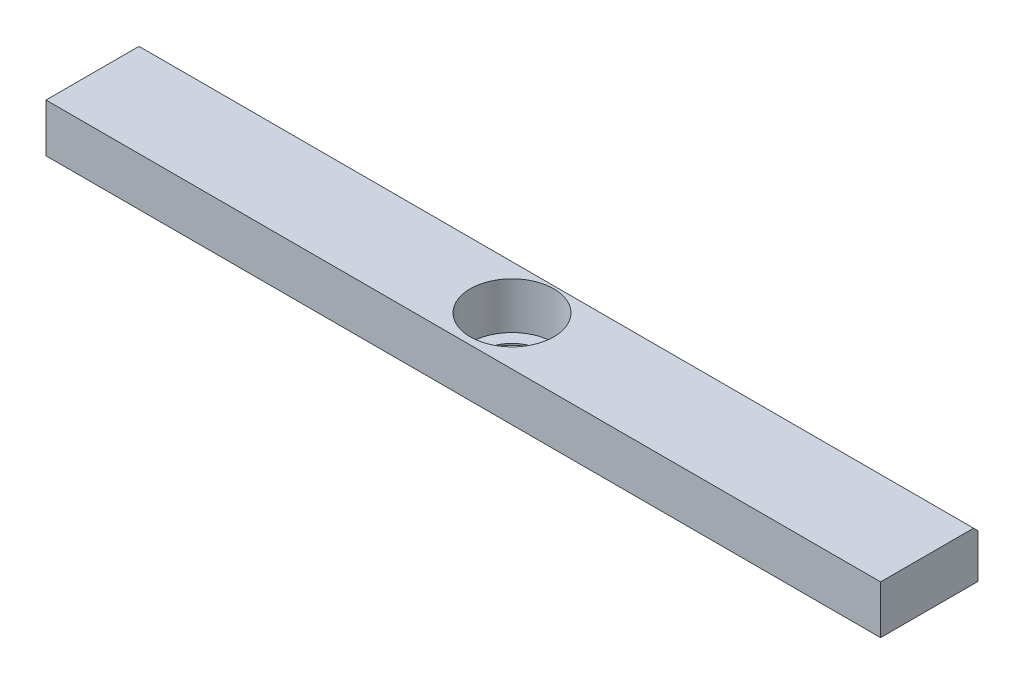
SolidWorks part; units mm, degrees
ref_plane "Front Plane" through (0, 0, 0) normal (0, 0, 1) x (1, 0, 0)
ref_plane "Top Plane" through (0, 0, 0) normal (0, 1, 0) x (1, 0, 0)
ref_plane "Right Plane" through (0, 0, 0) normal (1, 0, 0) x (0, 0, -1)
sketch "Sketch1" plane through (0, 0, 0) normal (0, 1, 0) x (1, 0, 0)
  line L0 (475, -55.4323) -> (475, -1055.4323) construction
  line L1 (475, -55.4323) -> (-475, -55.4323)
  line L2 (475, -55.4323) -> (475, 55.4323)
  line L3 (475, 55.4323) -> (-475, 55.4323)
  line L4 (-475, -55.4323) -> (-475, 55.4323)
  line L5 (475, -55.4323) -> (-475, 55.4323) construction
  line L6 (475, 55.4323) -> (-475, -55.4323) construction
  line L7 (475, -1055.4323) -> (-475, -1055.4323) construction
  line L8 (-475, -1055.4323) -> (-475, -55.4323) construction
  point P0 (0, 0)
  point P8 (-475, 55.4323)
  dimension "D1" = 950
  dimension "D2" = 1000
extrude "Boss-Extrude1" add sketch "Sketch1" along normal mid plane 55
sketch "Sketch2" plane through (0, 27.5, 0) normal (0, 1, 0) x (1, 0, 0)
  circle A0 centre (0, 0) radius 47.5
  dimension "D1" = 95
extrude "Cut-Extrude1" cut sketch "Sketch2" against normal blind 53
sketch "Sketch3" plane through (0, -25.5, 0) normal (0, 1, 0) x (1, 0, 0)
  circle A0 centre (0, 0) radius 32.5
  dimension "D1" = 65
extrude "Cut-Extrude2" cut sketch "Sketch3" against normal blind 53
chamfer "Chamfer1" distance 5 angle 45 1 edges at (0, 27.5, -55.4323)
